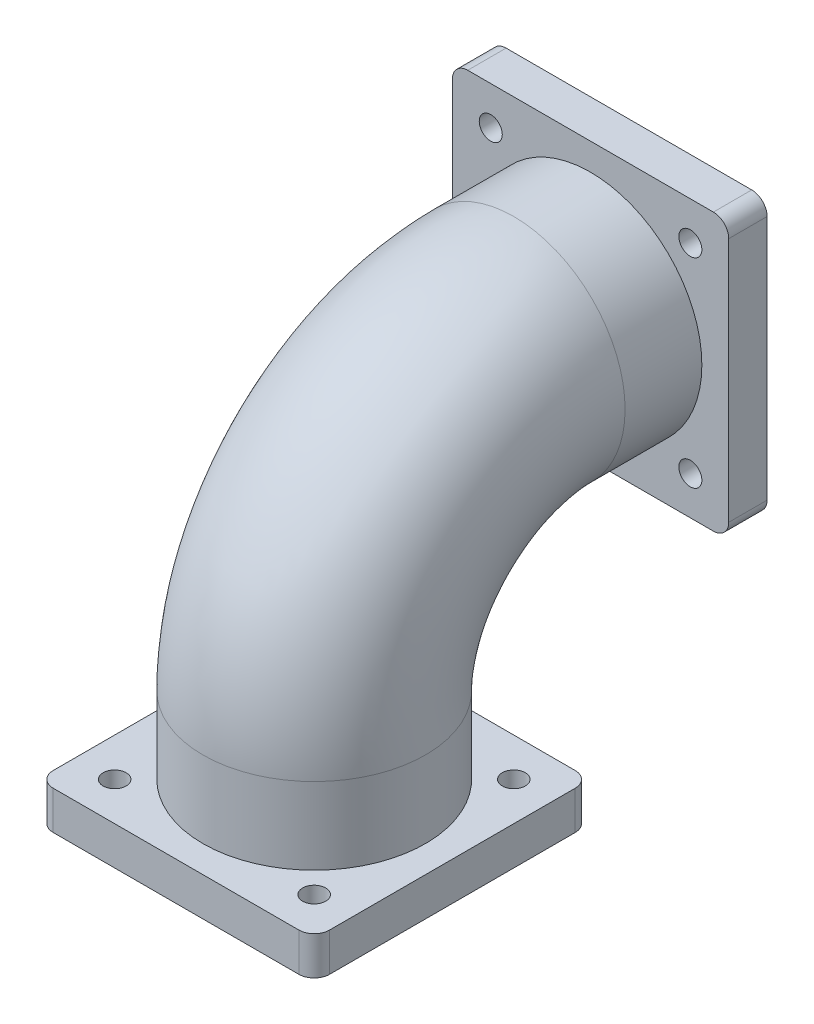
SolidWorks part; units mm, degrees
ref_plane "Front Plane" through (0, 0, 0) normal (0, 0, 1) x (1, 0, 0)
ref_plane "Top Plane" through (0, 0, 0) normal (0, 1, 0) x (1, 0, 0)
ref_plane "Right Plane" through (0, 0, 0) normal (1, 0, 0) x (0, 0, -1)
sketch "Sketch1" plane through (0, 0, 0) normal (0, 0, 1) x (1, 0, 0)
  line L1 (20, 0) -> (340, 0)
  line L2 (0, 20) -> (0, 340)
  line L3 (20, 360) -> (340, 360)
  line L4 (360, 20) -> (360, 340)
  circle A0 centre (50, 310) radius 15
  circle A1 centre (50, 310) radius 30
  circle A2 centre (180, 180) radius 105
  arc A3 (360, 340) -> (340, 360) centre (340, 340) ccw
  circle A5 centre (310, 310) radius 15
  circle A6 centre (310, 310) radius 30
  arc A7 (0, 20) -> (20, 0) centre (20, 20) ccw
  circle A8 centre (310, 50) radius 15
  circle A9 centre (310, 50) radius 30
  arc A10 (20, 360) -> (0, 340) centre (20, 340) ccw
  circle A11 centre (50, 50) radius 15
  circle A12 centre (50, 50) radius 30
  arc A13 (340, 0) -> (360, 20) centre (340, 20) ccw
  arc A14 (338.2573, 39.9239) -> (320.0761, 21.7427) centre (340, 20) ccw [skipped]
  point P12 (360, 180)
  point P31 (180, 180)
  dimension "D3" = 50
  dimension "D5" = 60
  dimension "D6" = 30
  dimension "D7" = 40
  dimension "D10" = 210
  dimension "D4" = 50
  dimension "D8" = 180
  dimension "D9" = 180
  dimension "D11" = 4
extrude "Boss-Extrude1" add sketch "Sketch1" along normal blind 50 contours L1 A13 L4 A3 L3 A10 L2 A7 A1 A2 A6 A9 A12 | A1 A0 | A6 A5 | A12 A11 | A9 A8
sketch "Sketch3" plane through (0, 0, 0) normal (0, 0, -1) x (-1, 0, 0)
  circle A0 centre (-50, 310) radius 30
  circle A1 centre (-50, 310) radius 15
  circle A2 centre (-310, 310) radius 15
  circle A3 centre (-310, 310) radius 30
  circle A4 centre (-310, 50) radius 15
  circle A5 centre (-310, 50) radius 30
  circle A6 centre (-50, 50) radius 15
  circle A7 centre (-50, 50) radius 30
extrude "Cut-Extrude1" cut sketch "Sketch3" against normal blind 10
ref_plane "Plane1" through (180, 0, 0) normal (-1, 0, 0) x (0, 0, 1)
sketch "Sketch5" plane through (0, 0, 50) normal (0, 0, 1) x (1, 0, 0)
  circle A0 centre (180, 180) radius 105
  circle A1 centre (180, 180) radius 145
  dimension "290" = 290
sketch "Sketch4" plane through (180, 0, 0) normal (1, 0, 0) x (0, 0, -1)
  line L0 (-50, 180) -> (-150, 180)
  line L1 (-50, 285) -> (-50, 75) construction
  line L2 (-410, -80) -> (-410, -230)
  line L4 (-50, 325) -> (-50, 35) construction
  arc A0 (-150, 180) -> (-410, -80) centre (-150, -80) ccw
  point P3 (0, 0)
  point P10 (0, 0)
  point P11 (0, 0)
  dimension "D2" = 520
  dimension "D3" = 150
sweep "Sweep1" add profiles "Sketch5" path "Sketch4"
sketch "Sketch6" plane through (180, 0, 0) normal (-1, 0, 0) x (0, 0, 1)
  line L0 (150, -80) -> (208.8077, -21.1923) construction
  line L2 (150, -80) -> (55.4121, -80)
  line L3 (50, 0) -> (0, 0) construction
  circle A0 centre (150, -80) radius 36.6882
  point P6 (172.7308, 0)
  dimension "D1" = 135
pattern_circular "CirPattern1" count 2 over 360 about axis through (180, -80, 150) along (0, 0.7071, 0.7071) of "Boss-Extrude1", "Cut-Extrude1"
